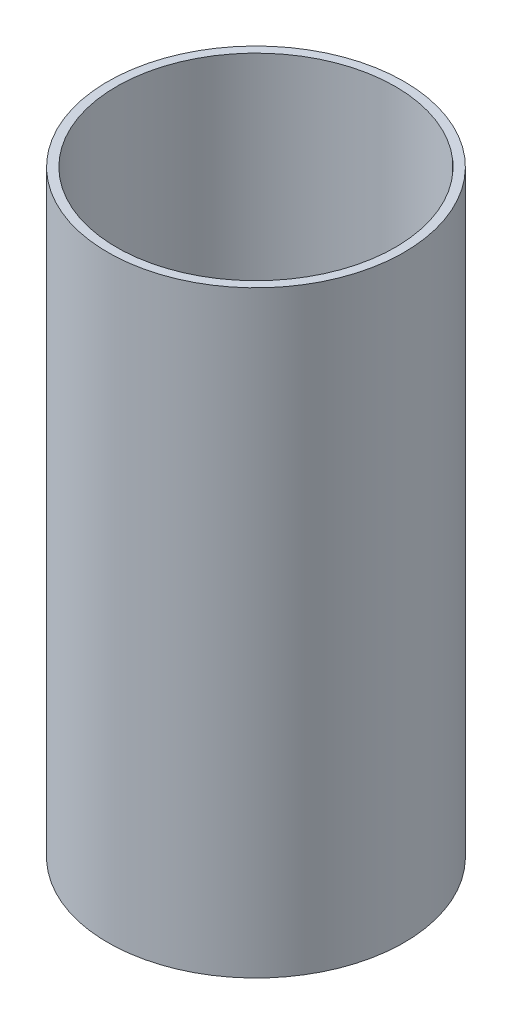
SolidWorks part; units mm, degrees
material "E-Glass Fiber"
ref_plane "Front Plane" through (0, 0, 0) normal (0, 0, 1) x (1, 0, 0)
ref_plane "Top Plane" through (0, 0, 0) normal (0, 1, 0) x (1, 0, 0)
ref_plane "Right Plane" through (0, 0, 0) normal (1, 0, 0) x (0, 0, -1)
sketch "Sketch1" plane through (0, 0, 0) normal (0, 0, 1) x (1, 0, 0)
  line L0 (0, 0) -> (0, 53.3818) construction
  line L1 (-26.9875, 7.0376) -> (26.9875, 7.0376) construction
  line L2 (25.4, 7.0376) -> (26.9875, 7.0376)
  line L3 (25.4, 7.0376) -> (25.4, -101.894)
  line L4 (25.4, -101.894) -> (26.9875, -101.894)
  line L5 (26.9875, 7.0376) -> (26.9875, -101.894)
  line L6 (26.9875, 7.0376) -> (26.9875, -145.3624) construction
  dimension "D1" = 1.5875
revolve "Revolve1" add sketch "Sketch1" angle 360 about L0
